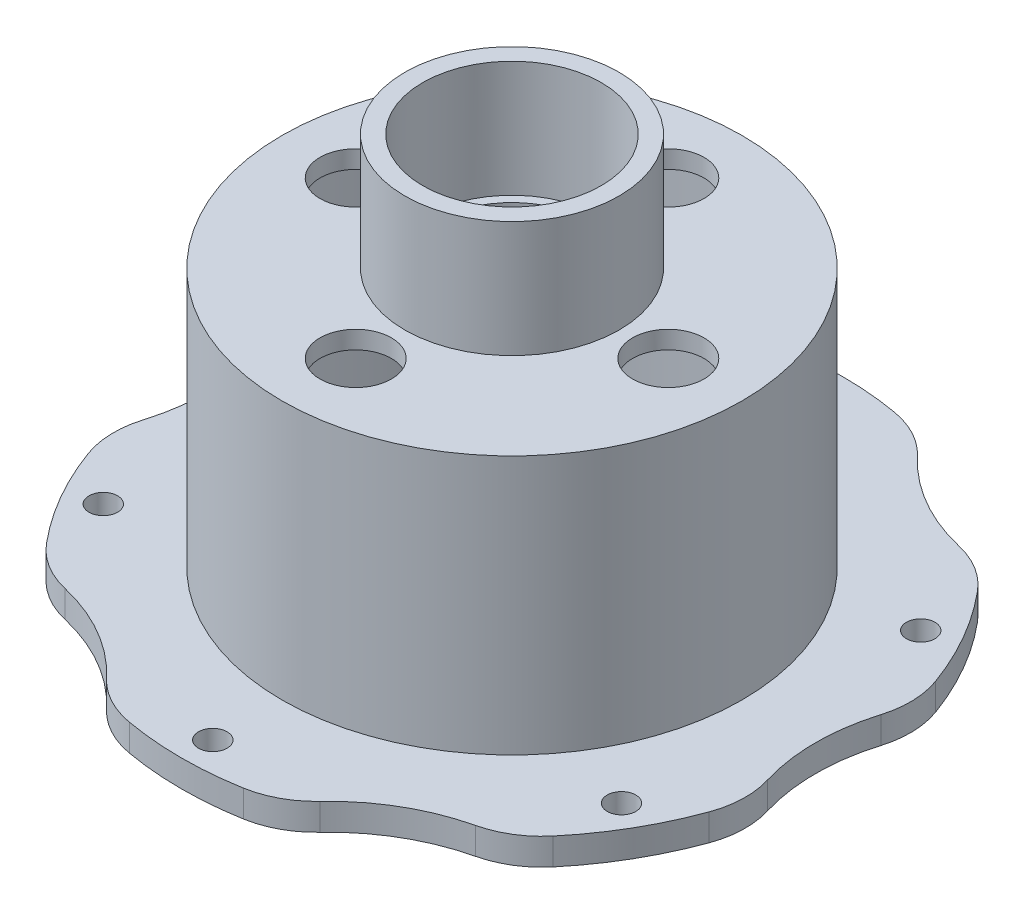
SolidWorks part; units mm, degrees
material "6060 合金"
ref_plane "前视基准面" through (0, 0, 0) normal (0, 0, 1) x (1, 0, 0)
ref_plane "上视基准面" through (0, 0, 0) normal (0, 1, 0) x (1, 0, 0)
ref_plane "右视基准面" through (0, 0, 0) normal (1, 0, 0) x (0, 0, -1)
sketch "草图1" plane through (0, 0, 0) normal (0, 1, 0) x (1, 0, 0)
  circle A0 centre (0, 0) radius 24
  circle A1 centre (0, 0) radius 25.75
  circle A2 centre (0, 0) radius 23 construction
  dimension "D1" = 48
  dimension "D2" = 51.5
  dimension "D3" = 46
extrude "凸台-拉伸1" add sketch "草图1" along normal blind 30
sketch "草图2" plane through (0, 0, 0) normal (0, -1, 0) x (1, 0, 0)
  line L0 (0, 0) -> (33.5, 0) construction
  circle A0 centre (0, 0) radius 31 construction
  circle A1 centre (0, 0) radius 37
  circle A2 centre (33.5, 0) radius 3.25 construction
  circle A4 centre (33.5, 0) radius 1.6 construction
  circle A5 centre (0, 0) radius 29 construction
  circle A6 centre (0, 0) radius 24 construction
  circle A7 centre (0, 0) radius 24
  dimension "D1" = 62
  dimension "D2" = 74
  dimension "D3" = 6.5
  dimension "D4" = 3.2
  dimension "D5" = 58
  dimension "D6" = 33.5
extrude "凸台-拉伸2" add sketch "草图2" against normal blind 3 contours A1
sketch "草图3" plane through (0, 0, 0) normal (0, -1, 0) x (1, 0, 0)
  circle A0 centre (0, 0) radius 29
  dimension "D1" = 58
extrude "切除-拉伸1" cut sketch "草图3" against normal blind 1
sketch "草图4" plane through (0, 3, 0) normal (0, 1, 0) x (1, 0, 0)
  line L0 (0, 33.5) -> (0, 0) construction
  circle A0 centre (0, 33.5) radius 1.6
  dimension "D1" = 3.2
  dimension "D2" = 33.5
extrude "切除-拉伸2" cut sketch "草图4" against normal blind 21
pattern_circular "阵列(圆周)1" count 6 over 360 about axis through (0, 0, 0) along (0, 1, 0) of "切除-拉伸2"
sketch "草图5" plane through (0, 0, 0) normal (0, -1, 0) x (1, 0, 0)
  line L0 (31, 0) -> (34, 0) construction
  circle A0 centre (56, 0) radius 22
  circle A1 centre (0, 0) radius 31 construction
  dimension "D1" = 44
  dimension "D3" = 62
  dimension "D2" = 56
extrude "切除-拉伸3" cut sketch "草图5" against normal blind 11
pattern_circular "阵列(圆周)2" count 6 over 360 about axis through (0, 0, 0) along (0, 1, 0) of "切除-拉伸3"
sketch "草图6" plane through (0, 30, 0) normal (0, 1, 0) x (1, 0, 0)
  circle A0 centre (0, 0) radius 25.75
  circle A1 centre (0, 0) radius 10
  circle A2 centre (0, 0) radius 25.75 construction
  dimension "D1" = 20
extrude "凸台-拉伸3" add sketch "草图6" along normal blind 2
sketch "草图7" plane through (0, 32, 0) normal (0, 1, 0) x (1, 0, 0)
  circle A0 centre (0, 0) radius 10
  circle A1 centre (0, 0) radius 12
  dimension "D1" = 24
  dimension "D2" = 20
extrude "凸台-拉伸4" add sketch "草图7" along normal blind 13
sketch "草图8" plane through (0, 32, 0) normal (0, 1, 0) x (1, 0, 0)
  line L0 (0, 17.5) -> (0, 0) construction
  circle A5 centre (0, 17.5) radius 4
  dimension "D1" = 8
  dimension "D2" = 17.5
extrude "切除-拉伸5" cut sketch "草图8" against normal blind 15.3
pattern_circular "阵列(圆周)4" count 4 over 360 about axis through (0, 0, 0) along (0, 1, 0) of "切除-拉伸5"
sketch "草图9" plane through (0, 30, 0) normal (0, -1, 0) x (1, 0, 0)
  circle A0 centre (0, 0) radius 10 construction
  circle A1 centre (0, 0) radius 10
  circle A2 centre (0, 0) radius 9
  dimension "D1" = 9
extrude "凸台-拉伸5" add sketch "草图9" against normal blind 2
fillet "圆角1" radius 10 12 edges at (35.9018, 1.5, 8.9477) (35.9018, 1.5, -8.9477) (10.2019, 1.5, 35.5657) (25.6999, 1.5, 26.618) (-25.6999, 1.5, 26.618) (-10.2019, 1.5, 35.5657) (-35.9018, 1.5, -8.9477) (-35.9018, 1.5, 8.9477) (-10.2019, 1.5, -35.5657) (-25.6999, 1.5, -26.618) (25.6999, 1.5, -26.618) (10.2019, 1.5, -35.5657)
